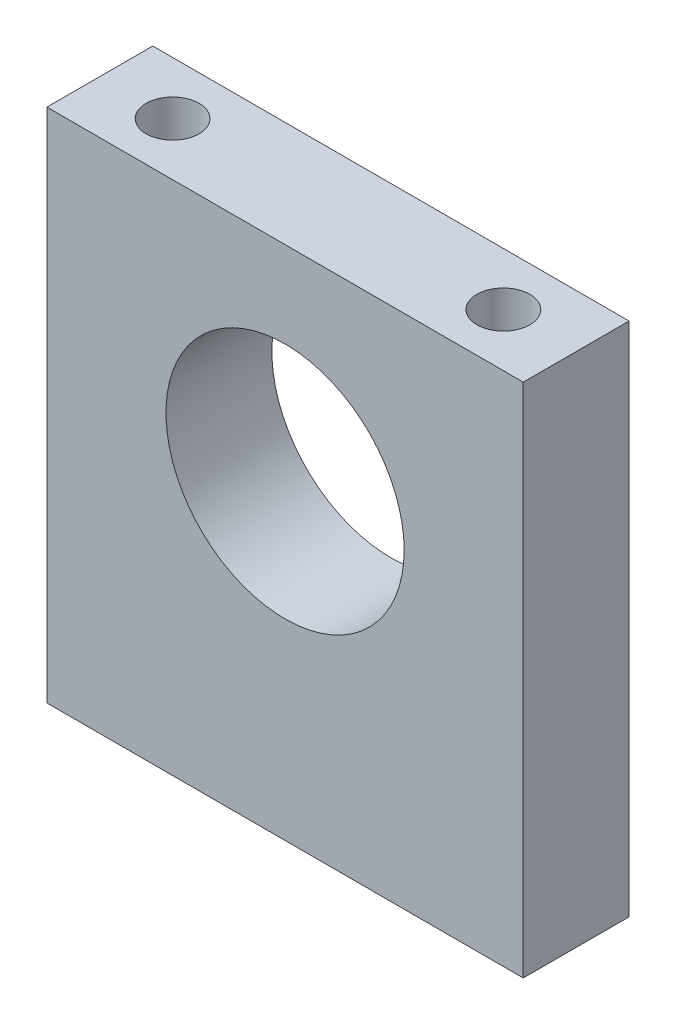
SolidWorks part; units mm, degrees
ref_plane "前视基准面" through (0, 0, 0) normal (0, 0, 1) x (1, 0, 0)
ref_plane "上视基准面" through (0, 0, 0) normal (0, 1, 0) x (1, 0, 0)
ref_plane "右视基准面" through (0, 0, 0) normal (1, 0, 0) x (0, 0, -1)
sketch "草图1" plane through (0, 0, 0) normal (0, 1, 0) x (1, 0, 0)
  line L1 (-18, 4) -> (18, 4)
  line L2 (-18, 4) -> (-18, -4)
  line L3 (-18, -4) -> (18, -4)
  line L4 (18, 4) -> (18, -4)
  line L5 (0, -4) -> (0, 4) construction
  line L6 (-18, 0) -> (18, 0) construction
  circle A0 centre (12.5, 0) radius 2
  circle A1 centre (-12.5, 0) radius 2
  point P0 (0, 0)
  dimension "D1" = 25
  dimension "D2" = 4
  dimension "D3" = 8
  dimension "D4" = 36
extrude "凸台-拉伸1" add sketch "草图1" along normal blind 39
sketch "草图3" plane through (0, 0, 4) normal (0, 0, 1) x (1, 0, 0)
  line L0 (0, 39) -> (0, 0) construction
  line L1 (-18, 39) -> (18, 39) construction
  line L2 (-18, 0) -> (18, 0) construction
  circle A0 centre (0, 23.5) radius 9
  dimension "D1" = 18
  dimension "D2" = 23.5
extrude "切除-拉伸1" cut sketch "草图3" against normal blind 10
